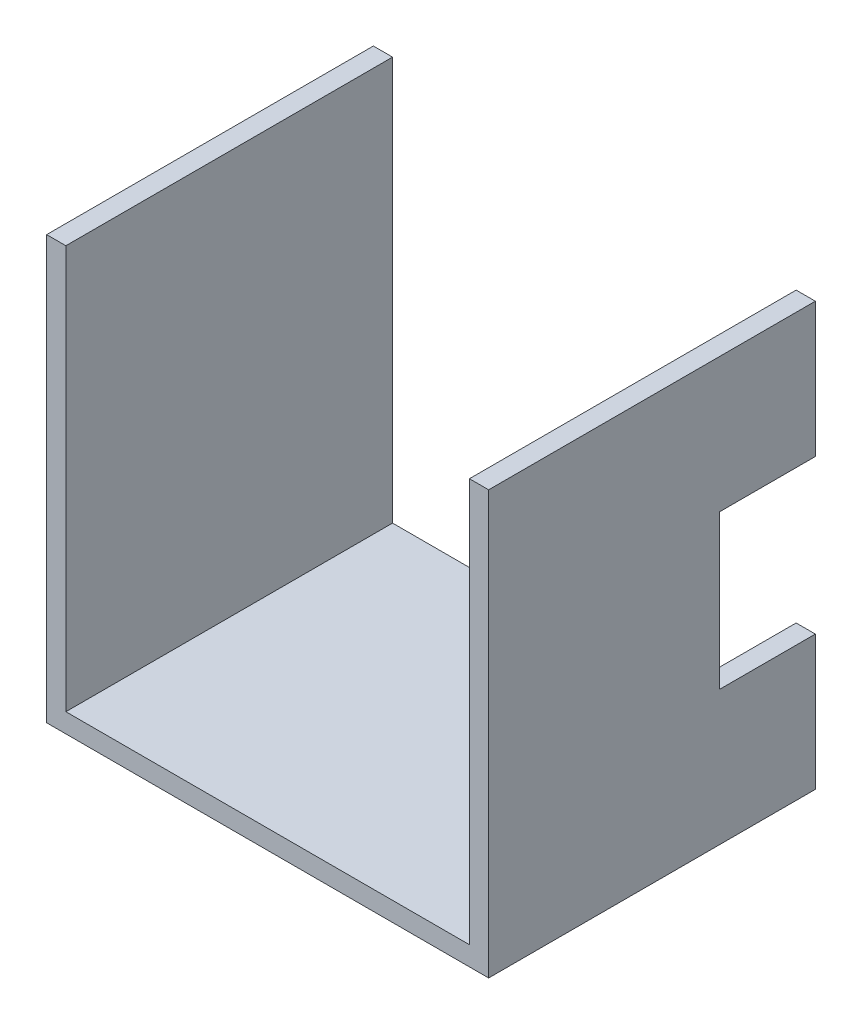
SolidWorks part; units mm, degrees
ref_plane "前视基准面" through (0, 0, 0) normal (0, 0, 1) x (1, 0, 0)
ref_plane "上视基准面" through (0, 0, 0) normal (0, 1, 0) x (1, 0, 0)
ref_plane "右视基准面" through (0, 0, 0) normal (1, 0, 0) x (0, 0, -1)
other "Configuration Table"
sketch "草图1" plane through (0, 0, 0) normal (0, 0, 1) x (1, 0, 0)
  line L0 (0, 42) -> (-2, 42)
  line L1 (0, 0) -> (42, 0)
  line L2 (0, 0) -> (0, 42)
  line L4 (42, 0) -> (42, 42)
  line L5 (-2, 42) -> (-2, -2)
  line L6 (-2, -2) -> (44, -2)
  line L7 (44, -2) -> (44, 42)
  line L8 (44, 42) -> (42, 42)
  dimension "D1" = 42
  dimension "D2" = 42
  dimension "D3" = 2
  dimension "D4" = 2
  dimension "D5" = 2
extrude "凸台-拉伸1" add sketch "草图1" along normal blind 34
sketch "草图2" plane through (44, 0, 0) normal (1, 0, 0) x (0, 0, -1)
  line L0 (0, -2) -> (0, 42) construction
  line L1 (0, 28) -> (0, 12)
  line L2 (0, 28) -> (-10, 28)
  line L3 (-10, 28) -> (-10, 12)
  line L4 (-10, 12) -> (0, 12)
  point P0 (0, 20)
  dimension "D1" = 16
  dimension "D2" = 8
  dimension "D3" = 10
extrude "切除-拉伸1" cut sketch "草图2" against normal blind 2
